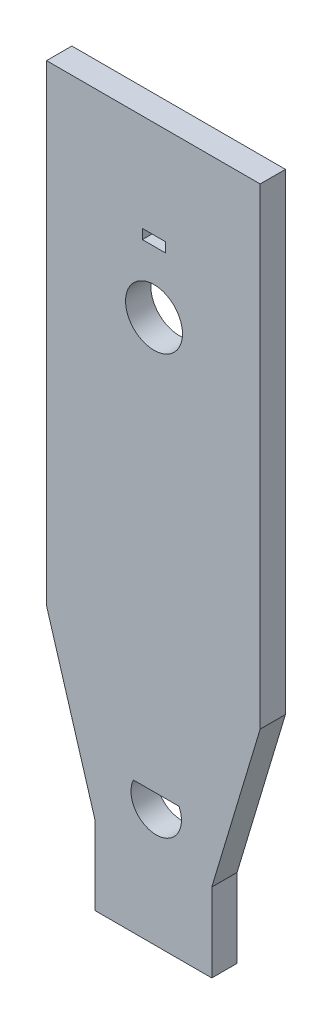
SolidWorks part; units mm, degrees
ref_plane "Front Plane" through (0, 0, 0) normal (0, 0, 1) x (1, 0, 0)
ref_plane "Top Plane" through (0, 0, 0) normal (0, 1, 0) x (1, 0, 0)
ref_plane "Right Plane" through (0, 0, 0) normal (1, 0, 0) x (0, 0, -1)
sketch "Model" plane through (0, 0, 0) normal (0, 0, 1) x (1, 0, 0)
  line L306 (-369.2066, 212.9265) -> (-369.2066, 257.1649)
  line L307 (-369.2066, 257.1649) -> (-343.8065, 257.1649)
  line L310 (-362.0525, 173.4925) -> (-369.2066, 212.9265)
  line L311 (-351.6601, 173.4925) -> (-343.8064, 213.5615)
  line L330 (-343.8064, 213.5615) -> (-343.8064, 257.1649)
  line L360 (-356.8563, 172.4499) -> (-356.5017, 172.178)
  line L361 (-356.5017, 172.178) -> (-356.0683, 172.2806)
  line L362 (-356.0683, 172.2806) -> (-355.8538, 171.8865)
  line L363 (-355.8538, 171.8865) -> (-355.4166, 171.8023)
  line L364 (-355.4166, 171.8023) -> (-355.3793, 171.3541)
  line L365 (-355.3793, 171.3541) -> (-355.0138, 171.0974)
  line L366 (-355.0138, 171.0974) -> (-355.1601, 170.6727)
  line L367 (-355.1601, 170.6727) -> (-354.9295, 170.288)
  line L368 (-354.9295, 170.288) -> (-355.2342, 169.96)
  line L369 (-355.2342, 169.96) -> (-355.1785, 169.5139)
  line L370 (-355.1785, 169.5139) -> (-355.5888, 169.3396)
  line L371 (-355.5888, 169.3396) -> (-355.7176, 168.909)
  line L372 (-355.7176, 168.909) -> (-356.1626, 168.9184)
  line L373 (-356.1626, 168.9184) -> (-356.4535, 168.578)
  line L374 (-356.4535, 168.578) -> (-356.8563, 168.7694)
  line L375 (-356.8563, 168.7694) -> (-357.2591, 168.578)
  line L376 (-357.2591, 168.578) -> (-357.55, 168.9184)
  line L377 (-357.55, 168.9184) -> (-357.995, 168.909)
  line L378 (-357.995, 168.909) -> (-358.1238, 169.3396)
  line L379 (-358.1238, 169.3396) -> (-358.5341, 169.5139)
  line L380 (-358.5341, 169.5139) -> (-358.4784, 169.96)
  line L381 (-358.4784, 169.96) -> (-358.7831, 170.288)
  line L382 (-358.7831, 170.288) -> (-358.5525, 170.6727)
  line L383 (-358.5525, 170.6727) -> (-358.6988, 171.0974)
  line L384 (-358.6988, 171.0974) -> (-358.3333, 171.3541)
  line L385 (-358.3333, 171.3541) -> (-358.296, 171.8023)
  line L386 (-358.296, 171.8023) -> (-357.8588, 171.8865)
  line L387 (-357.8588, 171.8865) -> (-357.6443, 172.2806)
  line L388 (-357.6443, 172.2806) -> (-357.2109, 172.178)
  line L389 (-357.2109, 172.178) -> (-356.8563, 172.4499)
  line L462 (-362.888, 248.8622) -> (-351.1786, 248.8622)
  line L463 (-351.1786, 248.8622) -> (-351.1786, 225.0624)
  line L464 (-351.1786, 225.0624) -> (-362.888, 225.0624)
  line L465 (-362.888, 225.0624) -> (-362.888, 248.8622)
  circle A0 centre (-357.0333, 223.3243) radius 0.9525
  spline S348 degree 3 poles (-362.0525, 173.4925) (-362.5791, 172.5803) (-362.8563, 171.5457) (-362.8563, 170.4925) knots 0 0 0 0 0.2 0.2 0.2 0.2
  spline S349 degree 3 poles (-362.8563, 170.4925) (-362.8563, 167.1788) (-360.1701, 164.4926) (-356.8563, 164.4926) knots 0.2 0.2 0.2 0.2 0.4 0.4 0.4 0.4
  spline S350 degree 3 poles (-356.8563, 164.4926) (-353.5425, 164.4926) (-350.8563, 167.1788) (-350.8563, 170.4925) knots 0.4 0.4 0.4 0.4 0.6 0.6 0.6 0.6
  spline S351 degree 3 poles (-350.8563, 170.4925) (-350.8563, 171.5457) (-351.1335, 172.5803) (-351.6601, 173.4925) knots 0.6 0.6 0.6 0.6 1 1 1 1
  spline S474 degree 3 poles (-357.9858, 223.3243) (-357.9858, 222.7982) (-357.5594, 222.3718) (-357.0333, 222.3718) knots 0 0 0 0 0.2 0.2 0.2 0.2
  spline S475 degree 3 poles (-357.0333, 222.3718) (-356.5072, 222.3718) (-356.0808, 222.7982) (-356.0808, 223.3243) knots 0.2 0.2 0.2 0.2 0.4 0.4 0.4 0.4
  spline S476 degree 3 poles (-356.0808, 223.3243) (-356.0808, 223.8504) (-356.5072, 224.2768) (-357.0333, 224.2768) knots 0.4 0.4 0.4 0.4 0.6 0.6 0.6 0.6
  spline S477 degree 3 poles (-357.0333, 224.2768) (-357.5594, 224.2768) (-357.9858, 223.8504) (-357.9858, 223.3243) knots 0.6 0.6 0.6 0.6 1 1 1 1
  spline S478 degree 3 poles (-357.9858, 250.6003) (-357.9858, 250.0742) (-357.5594, 249.6478) (-357.0333, 249.6478) knots 0 0 0 0 0.2 0.2 0.2 0.2
  spline S479 degree 3 poles (-357.0333, 249.6478) (-356.5072, 249.6478) (-356.0808, 250.0742) (-356.0808, 250.6003) knots 0.2 0.2 0.2 0.2 0.4 0.4 0.4 0.4
  spline S480 degree 3 poles (-356.0808, 250.6003) (-356.0808, 251.1264) (-356.5072, 251.5528) (-357.0333, 251.5528) knots 0.4 0.4 0.4 0.4 0.6 0.6 0.6 0.6
  spline S481 degree 3 poles (-357.0333, 251.5528) (-357.5594, 251.5528) (-357.9858, 251.1264) (-357.9858, 250.6003) knots 0.6 0.6 0.6 0.6 1 1 1 1
  dimension "D1" = 1.905
  dimension "D2" = 23.7998
  dimension "D3" = 11.7094
  dimension "D4" = 1.7381
  dimension "D5" = 92.6723
  dimension "D6" = 25.4002
sketch "Sketch1" plane through (0, 0, 0) normal (0, 0, 1) x (1, 0, 0)
  line L0 (-364.1237, 176.4925) -> (-369.8589, 195.5762)
  line L1 (-369.8589, 195.5762) -> (-369.8589, 251.556)
  line L2 (-369.8589, 251.556) -> (-344.532, 251.556)
  line L3 (-344.532, 251.556) -> (-344.532, 195.5762)
  line L4 (-344.532, 195.5762) -> (-350.2672, 176.4925)
  line L5 (-362.8563, 170.4925) -> (-350.8563, 170.4925) construction
  line L10 (-356.8563, 164.4926) -> (-356.8563, 181.556) construction
  line L11 (-356.8563, 164.4926) -> (-357.1955, 251.556) construction
  line L14 (-364.1237, 176.4925) -> (-364.1237, 167.1539)
  line L15 (-364.1237, 167.1539) -> (-350.2672, 167.1539)
  line L16 (-350.2672, 176.4925) -> (-350.2672, 167.1539)
  circle A0 centre (-357.1175, 231.556) radius 3.375
  circle A3 centre (-356.8563, 181.556) radius 3
  dimension "D3" = 14.4021
  dimension "D6" = 19.0837
  dimension "D11" = 6
  dimension "D8" = 6.75
  dimension "D2" = 50
  dimension "D4" = 9.3385
  dimension "D5" = 13.8565
  dimension "D7" = 55.9798
  dimension "D9" = 25.3268
extrude "Boss-Extrude3" add sketch "Sketch1" along normal blind 3
sketch "Sketch2" plane through (0, 0, 0) normal (0, 0, 1) x (1, 0, 0)
  circle A3 centre (-356.8563, 181.556) radius 3
  dimension "D11" = 6
sketch "Sketch4" plane through (0, 0, 3) normal (0, 0, 1) x (1, 0, 0)
sketch "Sketch5" plane through (0, 0, -9.5) normal (0, 0, 1) x (1, 0, 0)
  line L0 (-359.5563, 182.8406) -> (-354.1563, 182.8406)
  line L2 (-358.4975, 238.8591) -> (-355.7375, 238.8591)
  line L3 (-358.4975, 238.8591) -> (-358.4975, 240.0091)
  line L4 (-358.4975, 240.0091) -> (-355.7375, 240.0091)
  line L5 (-355.7375, 238.8591) -> (-355.7375, 240.0091)
  arc A0 (-359.5563, 182.8406) -> (-354.1563, 182.8406) centre (-356.8563, 181.549) ccw
extrude "Cut-Extrude3" cut sketch "Sketch5" along normal through all
equation "\"selftap\"=1.2"
